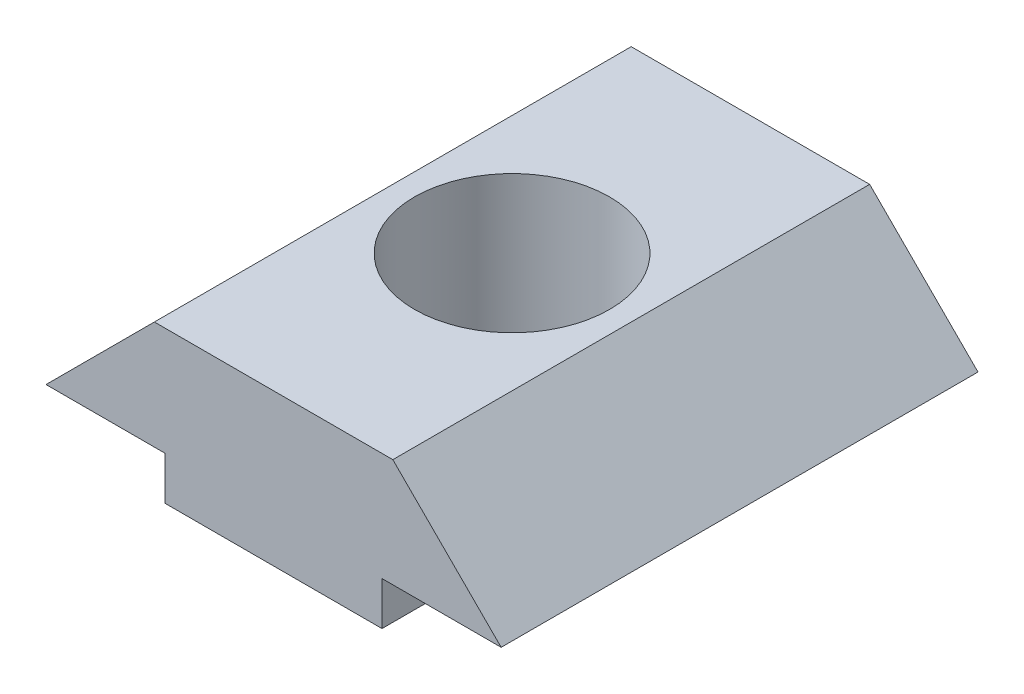
SolidWorks part; units mm, degrees
ref_plane "Plan de face" through (0, 0, 0) normal (0, 0, 1) x (1, 0, 0)
ref_plane "Plan de dessus" through (0, 0, 0) normal (0, 1, 0) x (1, 0, 0)
ref_plane "Plan de droite" through (0, 0, 0) normal (1, 0, 0) x (0, 0, -1)
sketch "Esquisse1" plane through (0, 0, 0) normal (0, 0, 1) x (1, 0, 0)
  line L1 (-2.5, 4.75) -> (2.501, 4.75)
  line L7 (-2.5, 4.75) -> (2.501, 4.75)
  line L8 (2.501, 4.75) -> (2.751, 4.75)
  line L9 (-2.5, 4.75) -> (-2.75, 4.75)
  line L10 (-4.5, 2.25) -> (-2.5, 2.25)
  line L11 (4.5, 2.25) -> (5.25, 2.25)
  line L12 (-4.5, 2.25) -> (-2.5, 2.25) construction
  line L13 (-4.5, 2.25) -> (-5.25, 2.25)
  line L14 (2.501, 2.25) -> (2.501, 1.25)
  line L15 (2.501, 1.25) -> (-2.5, 1.25)
  line L16 (-2.5, 2.25) -> (-2.5, 1.25)
  line L18 (2.501, 2.25) -> (4.5, 2.25)
  line L19 (2.751, 4.75) -> (5.25, 2.25)
  line L20 (-2.75, 4.75) -> (-5.25, 2.25)
  point P0 (0, 0)
  point P10 (6, -2.25)
  point P11 (-6, -2.25)
  dimension "D3" = 0.25
  dimension "D5" = 1
  dimension "D6" = 9
  dimension "D4" = 2
  dimension "D8" = 0.75
  dimension "D9" = 0.75
  dimension "D10" = 5.001
  dimension "D11" = 0.25
extrude "Boss.-Extru.1" add sketch "Esquisse1" along normal blind 11
sketch "Esquisse2" plane through (0, 1.25, 0) normal (0, -1, 0) x (1, 0, 0)
  line L0 (2.501, 11) -> (2.501, 0) construction
  line L1 (2.501, 0) -> (-2.5, 0) construction
  circle A0 centre (0.001, 5.5) radius 2.25
  point P2 (2.501, 5.5)
  dimension "D3" = 4.5
  dimension "D1" = 2.5
  dimension "D2" = 5.5
extrude "Enlèv. mat.-Extru.1" cut sketch "Esquisse2" against normal through all contours A0
